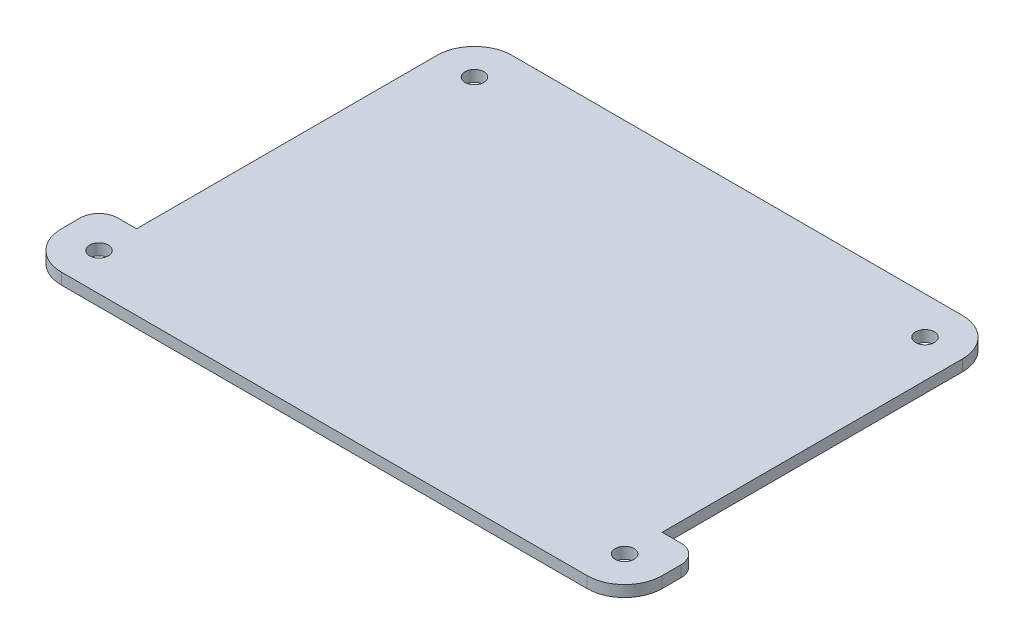
SolidWorks part; units mm, degrees
ref_plane "Alzado" through (0, 0, 0) normal (0, 0, 1) x (1, 0, 0)
ref_plane "Planta" through (0, 0, 0) normal (0, 1, 0) x (1, 0, 0)
ref_plane "Vista lateral" through (0, 0, 0) normal (1, 0, 0) x (0, 0, -1)
sketch "Croquis1" plane through (0, 0, 0) normal (0, 1, 0) x (1, 0, 0)
  line L0 (-70, 55) -> (-70, -55) construction
  line L1 (-60, 55) -> (60, 55)
  line L2 (-80, -40) -> (-80, -45)
  line L3 (-70, -55) -> (70, -55)
  line L4 (80, -40) -> (80, -45)
  line L5 (-80, 55) -> (80, -55) construction
  line L6 (-80, -55) -> (80, 55) construction
  line L7 (70, 55) -> (70, -55) construction
  line L8 (-80, -35) -> (80, -35) construction
  line L9 (-70, 45) -> (-70, -35)
  line L10 (-70, -35) -> (-75, -35)
  line L11 (70, 45) -> (70, -35)
  line L12 (70, -35) -> (75, -35)
  circle A0 centre (-60, 45) radius 2.5
  circle A1 centre (60, 45) radius 2.5
  circle A2 centre (-70, -45) radius 2.5
  circle A3 centre (70, -45) radius 2.5
  arc A4 (-70, 45) -> (-60, 55) centre (-60, 45) cw
  arc A5 (70, 45) -> (60, 55) centre (60, 45) ccw
  arc A6 (-70, -55) -> (-80, -45) centre (-70, -45) cw
  arc A7 (80, -45) -> (70, -55) centre (70, -45) cw
  arc A8 (-75, -35) -> (-80, -40) centre (-75, -40) ccw
  arc A9 (75, -35) -> (80, -40) centre (75, -40) cw
  point P0 (0, 0)
  point P6 (-60, 45)
  point P7 (60, 45)
  point P8 (70, -45)
  point P9 (-70, -45)
  point P22 (-70, -35)
  point P23 (70, -35)
  dimension "D11" = 5
  dimension "D12" = 5
  dimension "D13" = 5
  dimension "D14" = 5
  dimension "D2" = 10
  dimension "D17" = 10
  dimension "D18" = 10
  dimension "D19" = 10
  dimension "D20" = 5
  dimension "D21" = 5
  dimension "D1" = 160
  dimension "D3" = 20
  dimension "D4" = 10
  dimension "D5" = 20
  dimension "D6" = 10
  dimension "D7" = 10
  dimension "D8" = 10
  dimension "D9" = 10
  dimension "D10" = 10
  dimension "D15" = 10
  dimension "D16" = 10
extrude "Saliente-Extruir1" add sketch "Croquis1" along normal blind 3
